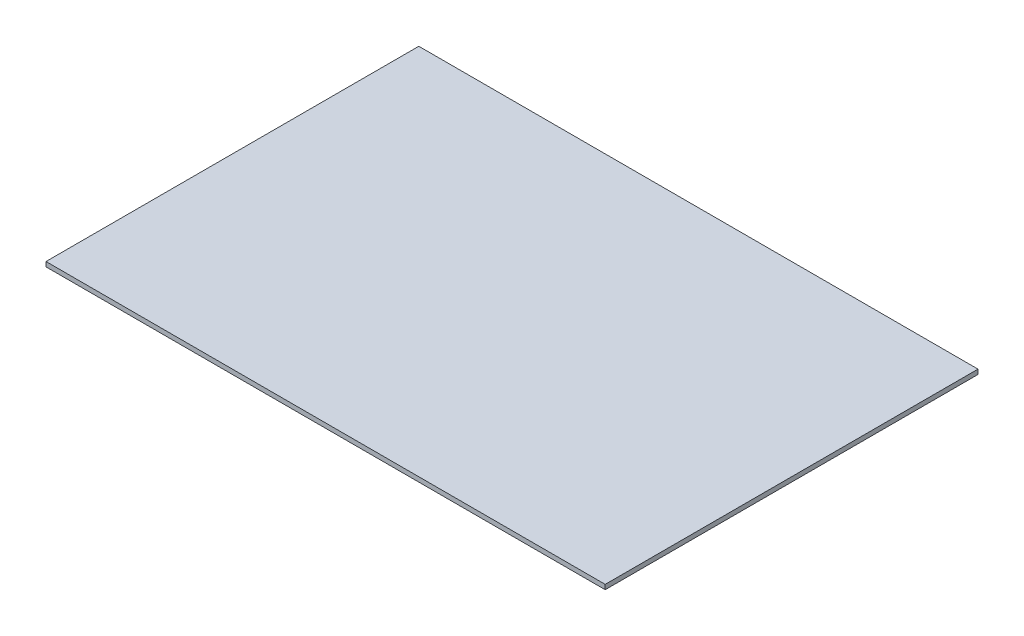
SolidWorks part; units mm, degrees
material "Glass"
ref_plane "Front Plane" through (0, 0, 0) normal (0, 0, 1) x (1, 0, 0)
ref_plane "Top Plane" through (0, 0, 0) normal (0, 1, 0) x (1, 0, 0)
ref_plane "Right Plane" through (0, 0, 0) normal (1, 0, 0) x (0, 0, -1)
sketch "Sketch1" plane through (0, 0, 0) normal (0, 1, 0) x (1, 0, 0)
  line L1 (0, 0) -> (304.8, 0)
  line L2 (0, 0) -> (0, 203.2)
  line L3 (0, 203.2) -> (304.8, 203.2)
  line L4 (304.8, 0) -> (304.8, 203.2)
  dimension "D1" = 203.2
  dimension "D2" = 304.8
extrude "Boss-Extrude1" add sketch "Sketch1" along normal blind 2.54
